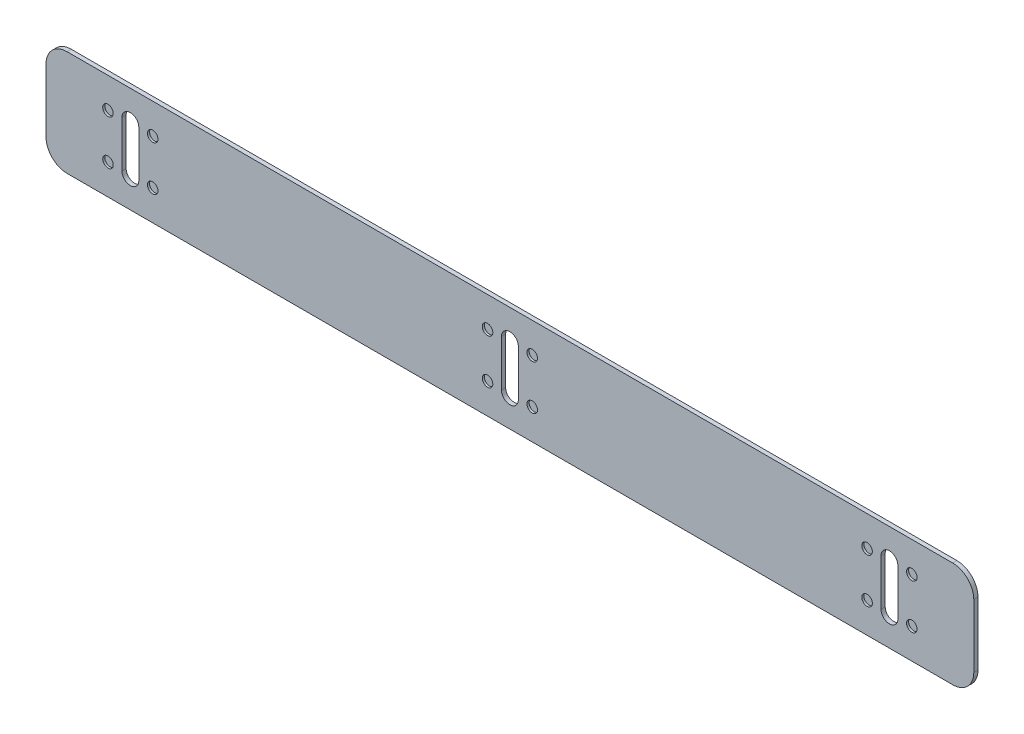
SolidWorks part; units mm, degrees
ref_plane "Plan de face" through (0, 0, 0) normal (0, 0, 1) x (1, 0, 0)
ref_plane "Plan de dessus" through (0, 0, 0) normal (0, 1, 0) x (1, 0, 0)
ref_plane "Plan de droite" through (0, 0, 0) normal (1, 0, 0) x (0, 0, -1)
sketch "Sketch1" plane through (0, 0, 0) normal (0, 0, 1) x (1, 0, 0)
  line L0 (-13.9833, 11.9444) -> (28.0167, 11.9444)
  line L1 (29.0167, 10.9444) -> (29.0167, 7.9444)
  line L2 (28.0167, 6.9444) -> (-13.9833, 6.9444)
  line L3 (-14.9833, 7.9444) -> (-14.9833, 10.9444)
  line L4 (25.0167, 9.4444) -> (7.0167, 9.4444) construction
  line L5 (-10.9833, 10.5444) -> (-10.9833, 8.3444) construction
  line L6 (7.0167, 9.4444) -> (-10.9833, 9.4444) construction
  line L7 (-10.5833, 10.5444) -> (-10.5833, 8.3444)
  line L8 (-11.3833, 10.5444) -> (-11.3833, 8.3444)
  line L9 (7.0167, 10.5444) -> (7.0167, 8.3444) construction
  line L10 (7.4167, 10.5444) -> (7.4167, 8.3444)
  line L11 (6.6167, 10.5444) -> (6.6167, 8.3444)
  line L12 (25.0167, 10.5444) -> (25.0167, 8.3444) construction
  line L13 (25.4167, 10.5444) -> (25.4167, 8.3444)
  line L14 (24.6167, 10.5444) -> (24.6167, 8.3444)
  arc A0 (28.0167, 11.9444) -> (29.0167, 10.9444) centre (28.0167, 10.9444) cw
  arc A1 (29.0167, 7.9444) -> (28.0167, 6.9444) centre (28.0167, 7.9444) cw
  arc A2 (-13.9833, 11.9444) -> (-14.9833, 10.9444) centre (-13.9833, 10.9444) ccw
  arc A3 (-13.9833, 6.9444) -> (-14.9833, 7.9444) centre (-13.9833, 7.9444) cw
  circle A4 centre (-10.9833, 9.4444) radius 1.5 construction
  circle A5 centre (7.0167, 9.4444) radius 1.5 construction
  circle A6 centre (25.0167, 9.4444) radius 1.5 construction
  arc A7 (-10.5833, 10.5444) -> (-11.3833, 10.5444) centre (-10.9833, 10.5444) ccw
  arc A8 (-11.3833, 8.3444) -> (-10.5833, 8.3444) centre (-10.9833, 8.3444) ccw
  arc A9 (7.4167, 10.5444) -> (6.6167, 10.5444) centre (7.0167, 10.5444) ccw
  arc A10 (6.6167, 8.3444) -> (7.4167, 8.3444) centre (7.0167, 8.3444) ccw
  arc A11 (25.4167, 10.5444) -> (24.6167, 10.5444) centre (25.0167, 10.5444) ccw
  arc A12 (24.6167, 8.3444) -> (25.4167, 8.3444) centre (25.0167, 8.3444) ccw
  point P3 (-14.9833, 9.4444)
  point P5 (-10.9833, 9.4444)
  point P11 (29.0167, 11.9444)
  point P16 (-14.9833, 11.9444)
  point P19 (-14.9833, 6.9444)
  point P27 (7.0167, 6.9444)
  point P31 (7.0167, 9.4444)
  point P32 (-10.9833, 7.9444)
  point P33 (-10.9833, 10.9444)
  point P41 (25.0167, 9.4444)
  dimension "D4" = 1
  dimension "D3" = 3
  dimension "D7" = 0.4
  dimension "D1" = 5
  dimension "D2" = 44
  dimension "D5" = 3
  dimension "D6" = 18
  dimension "D8" = 3
extrude "Boss-Extrude1" add sketch "Sketch1" along normal blind 0.2
sketch "Sketch2" plane through (0, 0, 0.2) normal (0, 0, 1) x (1, 0, 0)
  line L0 (-10.5833, 9.4444) -> (-11.3833, 9.4444) construction
  line L1 (-10.5833, 8.3444) -> (-10.5833, 10.5444) construction
  line L2 (-11.3833, 10.5444) -> (-11.3833, 8.3444) construction
  line L3 (-10.9833, 9.4444) -> (-9.9226, 10.5051) construction
  circle A0 centre (-10.9833, 9.4444) radius 1.5 construction
  circle A1 centre (-9.9226, 10.5051) radius 0.25
  circle A2 centre (-9.9226, 8.3838) radius 0.25
  circle A3 centre (-12.044, 8.3838) radius 0.25
  circle A4 centre (-12.044, 10.5051) radius 0.25
  circle A5 centre (8.0774, 10.5051) radius 0.25
  circle A6 centre (5.956, 10.5051) radius 0.25
  circle A7 centre (5.956, 8.3838) radius 0.25
  circle A8 centre (8.0774, 8.3838) radius 0.25
  circle A9 centre (26.0774, 10.5051) radius 0.25
  circle A10 centre (23.956, 10.5051) radius 0.25
  circle A11 centre (23.956, 8.3838) radius 0.25
  circle A12 centre (26.0774, 8.3838) radius 0.25
  point P19 (-10.9833, 9.4444)
  dimension "D1" = 0.5
  dimension "D3" = 3
  dimension "D2" = 4
extrude "Cut-Extrude1" cut sketch "Sketch2" against normal blind 0.1
